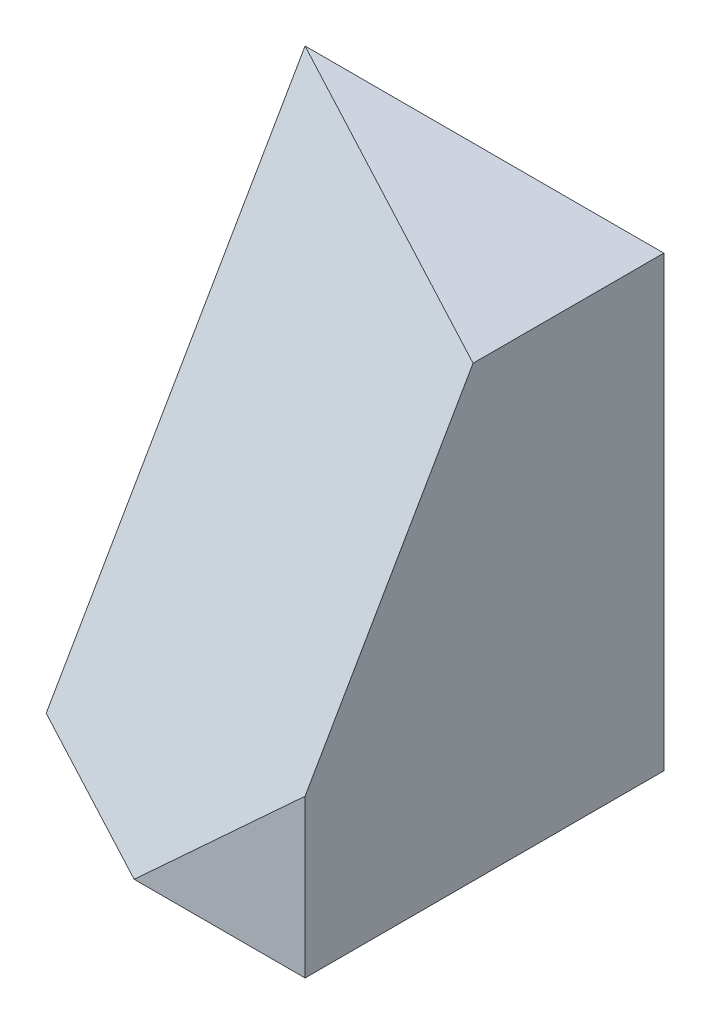
SolidWorks part; units mm, degrees
ref_plane "前视基准面" through (0, 0, 0) normal (0, 0, 1) x (1, 0, 0)
ref_plane "上视基准面" through (0, 0, 0) normal (0, 1, 0) x (1, 0, 0)
ref_plane "右视基准面" through (0, 0, 0) normal (1, 0, 0) x (0, 0, -1)
other "Configuration Table"
sketch "草图1" plane through (0, 0, 0) normal (0, 1, 0) x (1, 0, 0)
  line L1 (-24, 24) -> (24, 24)
  line L2 (-24, 24) -> (-24, -24)
  line L3 (-24, -24) -> (24, -24)
  line L4 (24, 24) -> (24, -24)
  line L5 (-24, 24) -> (24, -24) construction
  line L6 (-24, -24) -> (24, 24) construction
  point P0 (0, 0)
  dimension "D1" = 48
  dimension "D2" = 48
extrude "凸台-拉伸1" add sketch "草图1" along normal blind 60
sketch3d "3D草图1"
  line L0 (-24, 60, -24) -> (24, 60, 1.5221)
  line L1 (24, 60, 24) -> (24, 60, -24) construction
  line L2 (24, 60, 1.5221) -> (24, 21.0671, 24)
  line L5 (24, 60, 24) -> (24, 0, 24) construction
  line L6 (24, 21.0671, 24) -> (1.1246, 0, 24)
  line L10 (-24, 0, 24) -> (24, 0, 24) construction
  line L11 (1.1246, 0, 24) -> (-24, 0, 10.641)
  line L12 (-24, 0, -24) -> (-24, 0, 24) construction
  line L13 (-24, 0, 10.641) -> (-24, 60, -24)
  line L14 (24, 0, 24) -> (24, 0, -24) construction
  line L15 (-24, 60, -24) -> (-24, 60, 24) construction
  dimension "D1" = 62
  dimension "D2" = 60
  dimension "D3" = 62
  dimension "D4" = 60
ref_plane "基准面1" through (-7.6997, 8.3606, 14.481) normal (0.4183, -0.4542, -0.7866) x (-0.9083, -0.2091, -0.3622)
other "使用曲面切除1"
